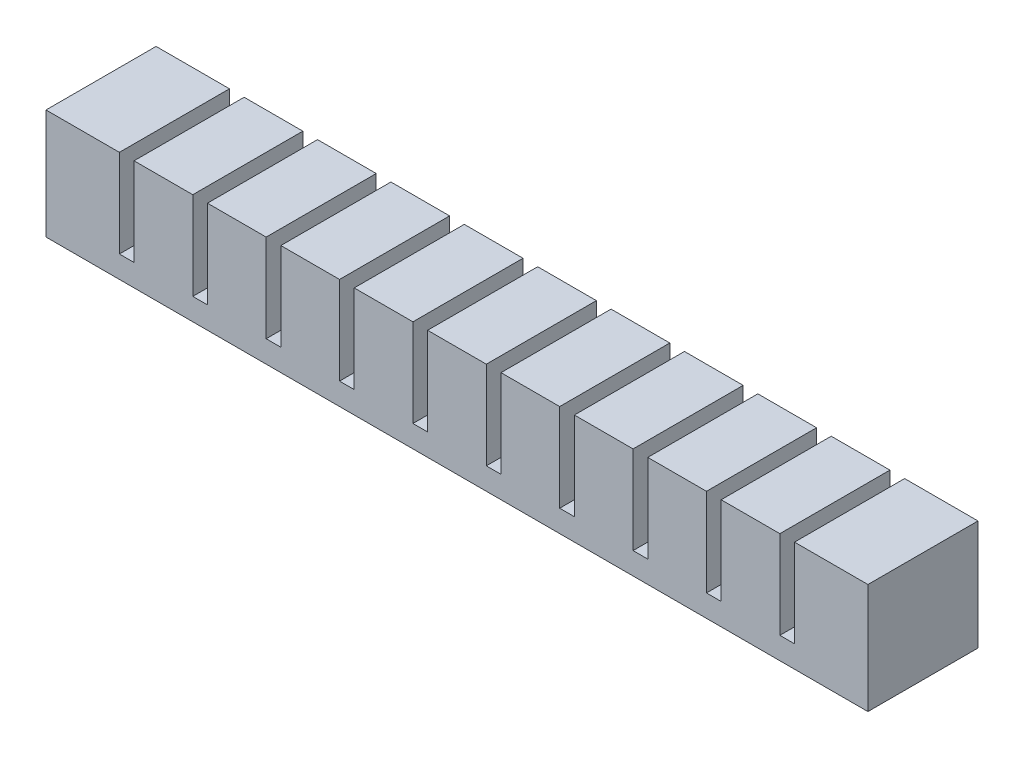
SolidWorks part; units mm, degrees
ref_plane "Front Plane" through (0, 0, 0) normal (0, 0, 1) x (1, 0, 0)
ref_plane "Top Plane" through (0, 0, 0) normal (0, 1, 0) x (1, 0, 0)
ref_plane "Right Plane" through (0, 0, 0) normal (1, 0, 0) x (0, 0, -1)
sketch "Sketch1" plane through (0, 0, 0) normal (0, 0, 1) x (1, 0, 0)
  line L1 (0, 0) -> (8, 0)
  line L2 (0, 0) -> (0, 15)
  line L3 (0, 15) -> (8, 15)
  line L4 (8, 0) -> (8, 15)
  dimension "D1" = 8
  dimension "D2" = 15
extrude "first chamber block" add sketch "Sketch1" along normal blind 15
sketch "Sketch2" plane through (0, 0, 0) normal (0, -1, 0) x (1, 0, 0)
  line L0 (8, 15) -> (8, 0) construction
  line L1 (1, 13) -> (7, 13)
  line L2 (1, 13) -> (1, 2)
  line L3 (1, 2) -> (7, 2)
  line L4 (7, 13) -> (7, 2)
  line L5 (0, 15) -> (0, 0) construction
  line L6 (0, 15) -> (8, 15) construction
  line L7 (0, 0) -> (8, 0) construction
  dimension "D1" = 1
  dimension "D2" = 1
  dimension "D3" = 2
  dimension "D4" = 2
extrude "first chamber cavity" cut sketch "Sketch2" against normal blind 13
sketch "Sketch3" plane through (8, 0, 0) normal (1, 0, 0) x (0, 0, -1)
  line L0 (-15, 0) -> (-15, 15) construction
  line L1 (0, 0) -> (-15, 0)
  line L2 (0, 0) -> (0, 3)
  line L3 (0, 3) -> (-15, 3)
  line L4 (-15, 0) -> (-15, 3)
  dimension "D1" = 3
extrude "chamber spacer" add sketch "Sketch3" along normal blind 2
pattern_linear "pattern chambers" count 11 spacing 10 along (1, 0, 0) of "chamber spacer", "first chamber cavity", "first chamber block"
combine bodies "combine into 1 solid body" operation type add bodies to combine 123 122 121 120 119 118 117 116 115 114 103
sketch "Sketch4" plane through (108, 0, 0) normal (1, 0, 0) x (0, 0, -1)
  line L1 (0, 15) -> (-15, 15)
  line L2 (0, 15) -> (0, 3)
  line L3 (0, 3) -> (-15, 3)
  line L4 (-15, 15) -> (-15, 3)
extrude "thicken end 1" add sketch "Sketch4" along normal up to surface (2 mm away) up to face at (110, 1.5, 7.5)
sketch "Sketch5" plane through (0, 0, 0) normal (-1, 0, 0) x (0, 0, 1)
  line L1 (15, 15) -> (0, 15)
  line L2 (15, 15) -> (15, 0)
  line L3 (15, 0) -> (0, 0)
  line L4 (0, 15) -> (0, 0)
extrude "thicken end 2" add sketch "Sketch5" along normal blind 2
ref_point "center of bottom face"
sketch "Sketch6" plane through (0, 0, 0) normal (0, -1, 0) x (1, 0, 0)
  line L0 (7, 2) -> (7, 13) construction
  line L1 (101, 6.5) -> (7, 6.5)
  line L2 (101, 6.5) -> (101, 8.5)
  line L3 (101, 8.5) -> (7, 8.5)
  line L4 (7, 6.5) -> (7, 8.5)
  line L5 (101, 6.5) -> (7, 8.5) construction
  line L6 (101, 8.5) -> (7, 6.5) construction
  point P0 (54, 7.5)
  dimension "D1" = 2
extrude "central air channel" cut sketch "Sketch6" against normal blind 2
sketch "Sketch7" plane through (0, 0, 0) normal (0, -1, 0) x (1, 0, 0)
  line L0 (0, 14) -> (108, 14)
  line L1 (1, 13) -> (107, 13)
  line L2 (1, 13) -> (1, 2)
  line L3 (1, 2) -> (107, 2)
  line L4 (107, 13) -> (107, 2)
  line L5 (108, 14) -> (108, 1)
  line L6 (0, 1) -> (108, 1)
  line L7 (0, 14) -> (0, 1)
  dimension "D1" = 1
extrude "bonding ridge" add sketch "Sketch7" along normal blind 2
sketch "Sketch9" plane through (0, 0, 0) normal (0, -1, 0) x (1, 0, 0)
  line L0 (11, 8.5) -> (11, 13) construction
  line L1 (11, 13) -> (7, 13) construction
  line L2 (7, 13) -> (7, 8.5) construction
  line L3 (7, 8.5) -> (11, 8.5) construction
  line L4 (7, 6.5) -> (7, 2) construction
  line L5 (7, 2) -> (11, 2) construction
  line L6 (11, 2) -> (11, 6.5) construction
  line L7 (11, 6.5) -> (7, 6.5) construction
  line L8 (11, 8.5) -> (11, 13) construction
  line L9 (11, 13) -> (7, 13) construction
  line L10 (7, 13) -> (7, 8.5) construction
  line L11 (7, 8.5) -> (11, 8.5) construction
  line L12 (7, 6.5) -> (7, 2) construction
  line L13 (7, 2) -> (11, 2) construction
  line L14 (11, 2) -> (11, 6.5) construction
  line L15 (11, 6.5) -> (7, 6.5) construction
  line L16 (10, 9.5) -> (10, 12)
  line L17 (10, 12) -> (8, 12)
  line L18 (8, 12) -> (8, 9.5)
  line L19 (8, 9.5) -> (10, 9.5)
  line L20 (8, 5.5) -> (8, 3)
  line L21 (8, 3) -> (10, 3)
  line L22 (10, 3) -> (10, 5.5)
  line L23 (10, 5.5) -> (8, 5.5)
  dimension "D1" = 1
extrude "bonding bumps" add sketch "Sketch9" along normal blind 2
pattern_linear "pattern bonding bumps" count 10 spacing 10 along (1, 0, 0) of "bonding bumps"
sketch "Skizze1" plane through (0, 0, 0) normal (0, -1, 0) x (1, 0, 0)
  line L4 (-2, 0) -> (110, 0)
  line L5 (110, 0) -> (110, 15)
  line L6 (110, 15) -> (-2, 15)
  line L7 (-2, 15) -> (-2, 0)
  line L8 (-2, 0) -> (110, 0)
  line L9 (110, 0) -> (110, 15)
  line L10 (110, 15) -> (-2, 15)
  line L11 (-2, 15) -> (-2, 0)
  dimension "D1" = 0
extrude "Schnitt-Linear austragen1" cut sketch "Skizze1" along normal through all
sketch "Skizze2" plane through (0, 3, 0) normal (0, 1, 0) x (1, 0, 0)
  line L0 (98, 0) -> (98, -15) construction
  line L1 (100, 0) -> (98, 0)
  line L2 (100, 0) -> (100, -1)
  line L3 (100, -1) -> (98, -1)
  line L4 (98, 0) -> (98, -1)
  line L5 (100, 0) -> (100, -15) construction
  line L6 (98, -15) -> (100, -15)
  line L7 (98, -15) -> (98, -14)
  line L8 (98, -14) -> (100, -14)
  line L9 (100, -15) -> (100, -14)
  dimension "D1" = 1
extrude "Aufsatz-Linear austragen1" [suppressed] add sketch "Skizze2" along normal offset from surface (9 mm away) 3
pattern_linear "Lineares Muster1" [suppressed] count 10 spacing 10
sketch "Skizze3" plane through (0, 0, 2) normal (0, 0, 1) x (1, 0, 0)
  line L0 (104, 0) -> (104, 13) construction
  line L1 (107, 0) -> (101, 0) construction
  line L2 (101, 13) -> (107, 13) construction
  circle A0 centre (104, 6.8582) radius 1.25
  dimension "D1" = 2.5
extrude "Schnitt-Linear austragen2" [suppressed] cut sketch "Skizze3" along normal through all
sketch "Skizze4" plane through (0, 0, 2) normal (0, 0, 1) x (1, 0, 0)
  line L0 (4, 13) -> (4, 0) construction
  line L1 (1, 13) -> (7, 13) construction
  line L2 (7, 0) -> (1, 0) construction
  circle A0 centre (4, 6.5) radius 1.25
  dimension "D1" = 2.5
extrude "Schnitt-Linear austragen3" cut sketch "Skizze4" against normal through all
